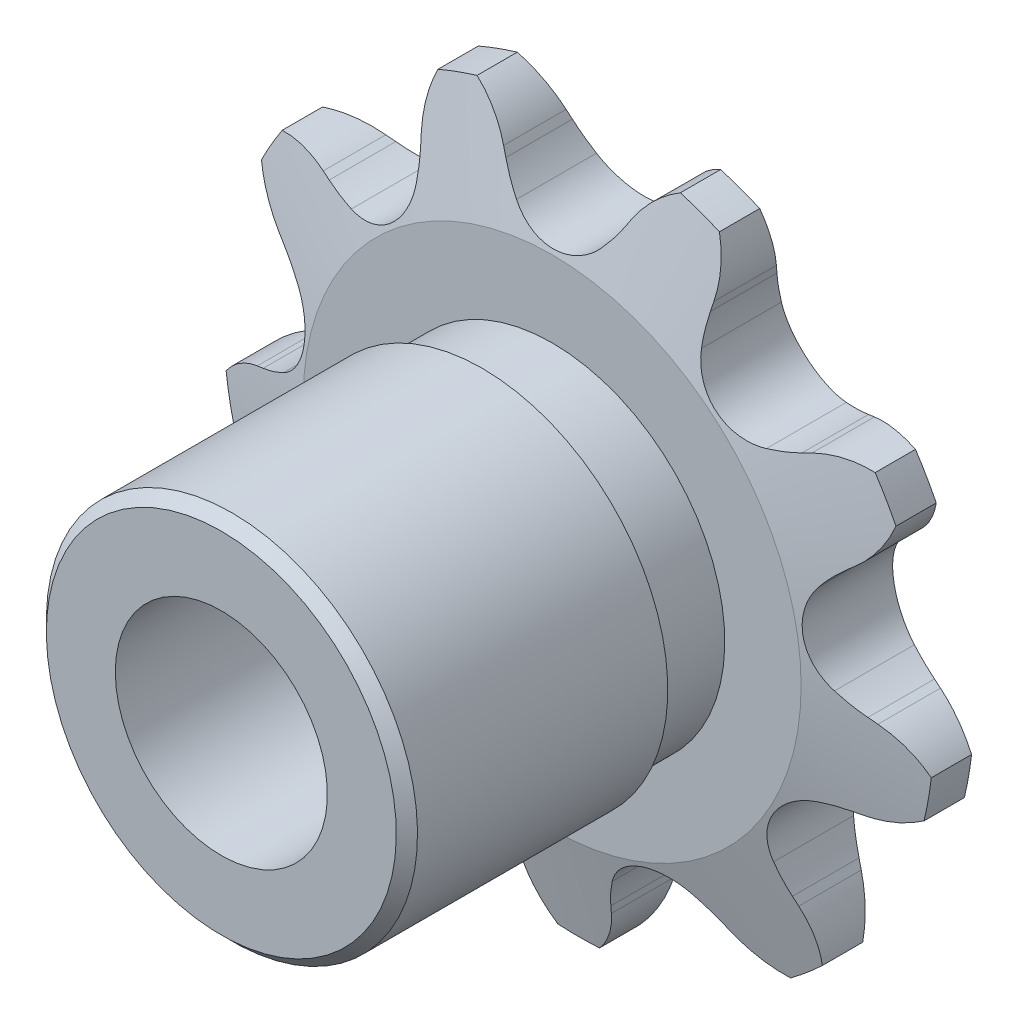
SolidWorks part; units mm, degrees
material "1023 Carbon Steel Sheet (SS)"
ref_plane "Front Plane" through (0, 0, 0) normal (0, 0, 1) x (1, 0, 0)
ref_plane "Top Plane" through (0, 0, 0) normal (0, 1, 0) x (1, 0, 0)
ref_plane "Right Plane" through (0, 0, 0) normal (1, 0, 0) x (0, 0, -1)
sketch "Sketch0" plane through (0, 0, 0) normal (0, 0, 1) x (1, 0, 0)
  line L0 (3.175, -8.7232) -> (0, 0) construction
  line L1 (0, 0) -> (8.0394, -4.6415) construction
  line L2 (0, 0) -> (-3.175, -8.7232) construction
  line L3 (3.175, -8.7232) -> (8.0394, -4.6415) construction
  line L4 (3.175, -8.7232) -> (-3.175, -8.7232) construction
  line L5 (4.9116, -7.8941) -> (4.7168, -7.73)
  line L6 (3.175, -8.7232) -> (0, -9.8788) construction
  line L7 (1.3117, -9.2043) -> (1.3555, -8.9534)
  line L8 (0, -8.7232) -> (0, -10.6282) construction
  line L9 (3.9806, -7.2292) -> (1.9213, -11.0484) construction
  line L10 (0, 0) -> (0, -8.7232) construction
  line L11 (4.7168, -7.73) -> (1.9213, -11.0484) construction
  line L12 (0, -10.6282) -> (0, -11.1212) construction
  line L13 (6.7163, -5.7518) -> (4.9116, -7.8941) construction
  circle A0 centre (0, 0) radius 10.6282 construction
  circle A1 centre (0, 0) radius 9.2831 construction
  arc A2 (-1.9064, -11.4866) -> (8.8438, -7.5738) centre (0, 0) ccw
  circle A3 centre (0, 0) radius 11.1212 construction
  circle A4 centre (3.175, -8.7232) radius 1.651 construction
  arc A7 (3.9806, -7.2292) -> (1.5976, -8.0966) centre (3.175, -8.7232) ccw
  circle A8 centre (3.175, -8.7232) radius 1.6974 construction
  arc A9 (4.9116, -7.8941) -> (8.8438, -7.5738) centre (6.7163, -5.7518) ccw
  arc A10 (4.7168, -7.73) -> (3.9806, -7.2292) centre (1.9213, -11.0484) ccw
  arc A11 (1.3117, -9.2043) -> (-1.9064, -11.4866) centre (-1.4478, -8.7232) cw
  arc A12 (1.3555, -8.9534) -> (1.5976, -8.0966) centre (5.63, -9.6985) cw
  dimension "D1" = 1.6974
  dimension "R" = 1.6974
sketch "Sketch1" plane through (0, 0, 0) normal (1, 0, 0) x (0, 0, -1)
  line L0 (1.397, 0) -> (-1.397, 0)
  line L1 (-1.397, 0) -> (-1.397, 7.4532)
  line L2 (-1.397, 7.4532) -> (-0.6033, 10.6282)
  line L3 (-0.6033, 10.6282) -> (0.6033, 10.6282)
  line L4 (0.6033, 10.6282) -> (1.397, 7.4532)
  line L5 (1.397, 7.4532) -> (1.397, 0)
  line L7 (0, 10.6282) -> (0, 0) construction
  line L8 (-1.397, 7.4532) -> (1.397, 7.4532) construction
  line L9 (0, 10.6282) -> (0, -10.6282) construction
  line L10 (-1.397, 7.4532) -> (-1.397, 10.6282) construction
  line L11 (-1.397, 10.6282) -> (-0.6033, 10.6282) construction
  line L12 (0.6033, 10.6282) -> (1.397, 10.6282) construction
  line L13 (1.397, 10.6282) -> (1.397, 7.4532) construction
  line L14 (0, 0) -> (-6.4008, 0) construction
  line L22 (1.397, 0) -> (-11.303, 0) construction
  line L24 (-1.397, 0) -> (-1.397, 5.1672) construction
revolve "Revolve1" add sketch "Sketch1" angle 360 mid plane about L0
extrude "Cut-Extrude1" cut sketch "Sketch0" against normal through all and the other way through all
pattern_circular "CirPattern1" count 9 over 360 about axis through (0, 0, 0) along (0, 0, 1) of "Cut-Extrude1"
sketch "Sketch2" plane through (0, 0, 0) normal (0, 0, 1) x (1, 0, 0)
  circle A0 centre (0, 0) radius 3.175 construction
  circle A1 centre (0, 0) radius 5.5562
  circle A2 centre (0, 0) radius 10.668 construction
  dimension "Bore" = 6.35
  dimension "Hub Dia." = 11.1125
  dimension "OD" = 21.336
extrude "Boss-Extrude1" add sketch "Sketch2" along normal up to vertex (11.303 mm away) from surface at 1.397 starting at face at (-7.4532, 0, 1.397)
sketch "Sketch3" plane through (0, 0, 0) normal (0, 0, 1) x (1, 0, 0)
  circle A0 centre (0, 0) radius 3.175 construction
  circle A1 centre (0, 0) radius 3.175
extrude "Cut-Extrude2" cut sketch "Sketch3" along normal through all and the other way through all
sketch "Sketch4" plane through (0, 0, 0) normal (1, 0, 0) x (0, 0, -1)
  line L0 (-11.303, 5.5562) -> (-11.303, 5.2387)
  line L1 (-1.397, 10.6282) -> (-3.4925, 10.6282)
  line L2 (-1.397, 10.6282) -> (-1.397, 5.1672)
  line L3 (-1.397, 5.1672) -> (-3.4925, 5.1672)
  line L4 (-3.4925, 10.6282) -> (-3.4925, 5.1672)
  line L9 (-11.303, 5.2387) -> (-10.9855, 5.5562)
  line L10 (-10.9855, 5.5562) -> (-11.303, 5.5562)
  dimension "C" = 0.3175
  dimension "D3" = 2.0955
revolve "Cut-Revolve1" cut sketch "Sketch4" angle 360 mid plane about L22
equation "\"360/N@Sketch0\" = 360/\"Teeth@CirPattern1\""
equation "\"Ds@Sketch0\" = 1.005 * \"Dr@Sketch0\" + 0.003"
equation "\"R@Sketch0\" = 1/2 * \"Ds@Sketch0\""
equation "\"A@Sketch0\" = 35 +  ( 60 / \"Teeth@CirPattern1\" ) "
equation "\"B@Sketch0\" = 18 -  ( 56 / \"Teeth@CirPattern1\" )"
equation "\"ac@Sketch0\" = 0.8 * \"Dr@Sketch0\""
equation "\"ab@Sketch0\" = 1.4 * \"Dr@Sketch0\""
equation "\"J@Sketch0\" = 0.3 * \"Pitch@Sketch0\""
equation "\"h@Sketch1\" = \"Pitch@Sketch0\" / 2"
equation "\"g@Sketch1\" = \"h@Sketch1\" / 4"
equation "\"MHD@Sketch1\" = \"Pitch@Sketch0\" * ( cotan ( 180 / \"Teeth@CirPattern1\" ) - 1 ) - 0.030"
equation "\"D3@Sketch4\" = \"t@Sketch1\" * 3 / 4"
